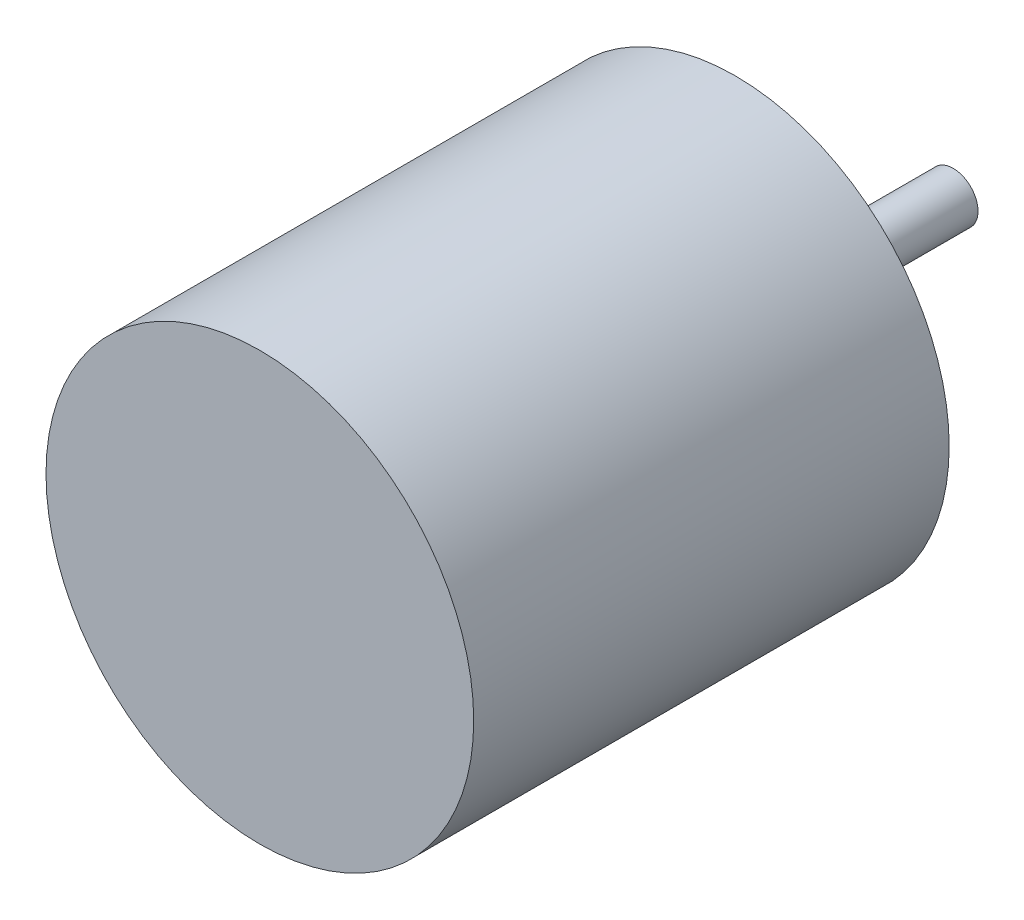
SolidWorks part; units mm, degrees
material "MOTORONLY"
ref_plane "Front Plane" through (0, 0, 0) normal (0, 0, 1) x (1, 0, 0)
ref_plane "Top Plane" through (0, 0, 0) normal (0, 1, 0) x (1, 0, 0)
ref_plane "Right Plane" through (0, 0, 0) normal (1, 0, 0) x (0, 0, -1)
other "Center of Mass"
sketch "Sketch1" plane through (0, 0, 0) normal (0, 0, 1) x (1, 0, 0)
  circle A0 centre (0, 0) radius 21.59
  dimension "D1" = 43.18
extrude "Boss-Extrude1" add sketch "Sketch1" along normal blind 48 contours A0
sketch "Sketch2" plane through (0, 0, 0) normal (0, 0, -1) x (-1, 0, 0)
  circle A0 centre (0, 0) radius 2.5
  dimension "D1" = 5
extrude "Boss-Extrude2" add sketch "Sketch2" along normal blind 22
equation "\"Motor_Diameter\" = 1.7"
equation "\"D1@Sketch1\"=\"Motor_Diameter\""
equation "\"Motor_Depth\"= 48mm"
equation "\"D1@Boss-Extrude1\"=\"Motor_Depth\""
equation "\"Shaft_Diameter\"=0.19685"
equation "\"Shaft_Length\"= 22mm"
equation "\"D1@Boss-Extrude2\"=\"Shaft_Length\""
equation "\"D1@Sketch2\"=\"Shaft_Diameter\""
